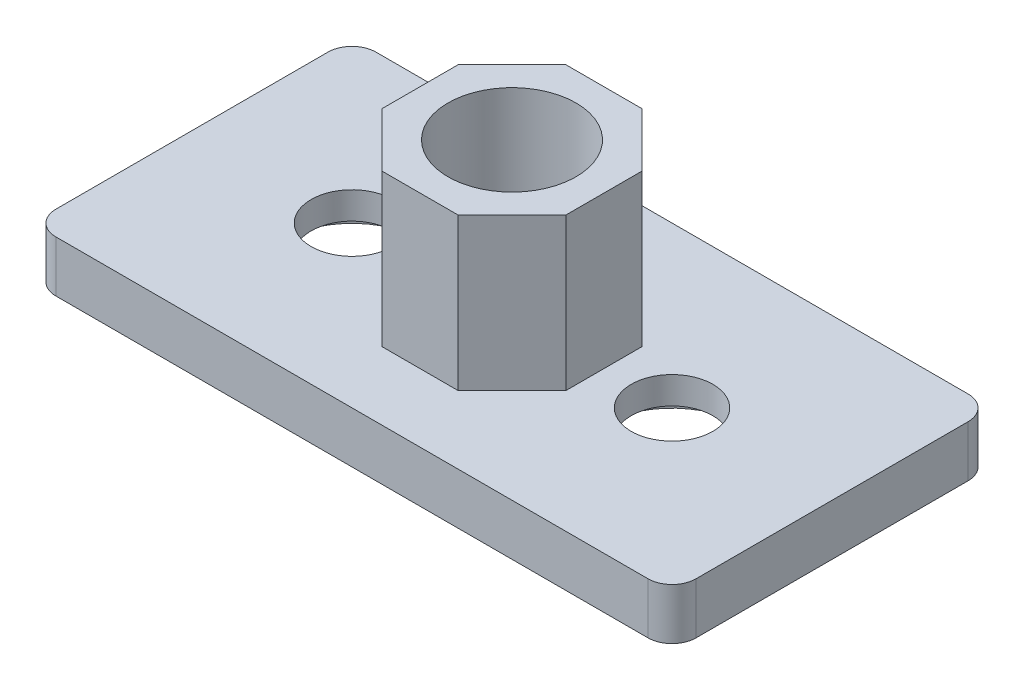
SolidWorks part; units mm, degrees
material "Delrin 2700 NC010, Low Viscosity Acetal Copolymer (SS)"
ref_plane "Front Plane" through (0, 0, 0) normal (0, 0, 1) x (1, 0, 0)
ref_plane "Top Plane" through (0, 0, 0) normal (0, 1, 0) x (1, 0, 0)
ref_plane "Right Plane" through (0, 0, 0) normal (1, 0, 0) x (0, 0, -1)
ref_plane "Plane1" through (0, -1.6, 0) normal (0, -1, 0) x (1, 0, 0)
sketch "Sketch1" plane through (0, -1.6, 0) normal (0, -1, 0) x (1, 0, 0)
  line L0 (-20, 0) -> (20, 0)
  line L1 (20, 0) -> (20, 20)
  line L2 (20, 20) -> (-20, 20)
  line L3 (-20, 20) -> (-20, 0)
extrude "Boss-Extrude1" add sketch "Sketch1" against normal blind 3.2
sketch "Sketch2" plane through (0, 1.6, 0) normal (0, 1, 0) x (-1, 0, 0)
  line L0 (-5.75, 12.3817) -> (-2.3817, 15.75)
  line L1 (-2.3817, 15.75) -> (2.3817, 15.75)
  line L2 (2.3817, 15.75) -> (5.75, 12.3817)
  line L3 (5.75, 12.3817) -> (5.75, 7.6183)
  line L4 (5.75, 7.6183) -> (2.3817, 4.25)
  line L5 (2.3817, 4.25) -> (-2.3817, 4.25)
  line L6 (-2.3817, 4.25) -> (-5.75, 7.6183)
  line L7 (-5.75, 7.6183) -> (-5.75, 12.3817)
extrude "Boss-Extrude2" add sketch "Sketch2" along normal blind 9.5
hole_wizard "Ø8.0 (8) Diameter Hole1" positions "Sketch4" profile "Sketch3" hole size "Ø8.0" standard "ANSI Metric"
sketch "Sketch4" plane through (0, -1.6, 0) normal (0, -1, 0) x (-1, 0, 0)
  point P0 (0, -10)
sketch "Sketch3" plane through (0, -1.6, 10) normal (1, 0, 0) x (0, 0, -1)
  line L0 (0, 0) -> (0, 12.7)
  line L1 (0, 12.7) -> (4, 12.7)
  line L2 (4, 12.7) -> (4, 0)
  line L5 (4, 0) -> (0, 0)
  line L11 (0, -6.35) -> (0, 107.95) construction
  dimension "Thru Hole Dia." = 8
  dimension "Thru Hole Depth" = 12.7
hole_wizard "Hole1" positions "Sketch6" profile "Sketch5" legacy
sketch "Sketch6" plane through (0, -1.6, 0) normal (0, -1, 0) x (-1, 0, 0)
  point P0 (10, -10)
  point P1 (-10, -10)
sketch "Sketch5" plane through (-10, -1.6, 10) normal (1, 0, 0) x (0, 0, -1)
  line L0 (0, 0) -> (0, 12.7)
  line L1 (0, 12.7) -> (2.55, 12.7)
  line L2 (2.55, 12.7) -> (2.55, 1.5)
  line L3 (2.55, 1.5) -> (4.5, 1.5)
  line L4 (4.5, 1.5) -> (4.5, 0)
  line L5 (4.5, 0) -> (0, 0)
  line L6 (0, 110) -> (0, -10) construction
  dimension "Diameter" = 5.1
  dimension "Depth" = 12.7
  dimension "C-Bore Diameter" = 9
  dimension "C-Bore Depth" = 1.5
fillet "Fillet1" radius 1.5 4 edges at (20, 0, 0) (-20, 0, 0) (20, 0, 20) (-20, 0, 20)
